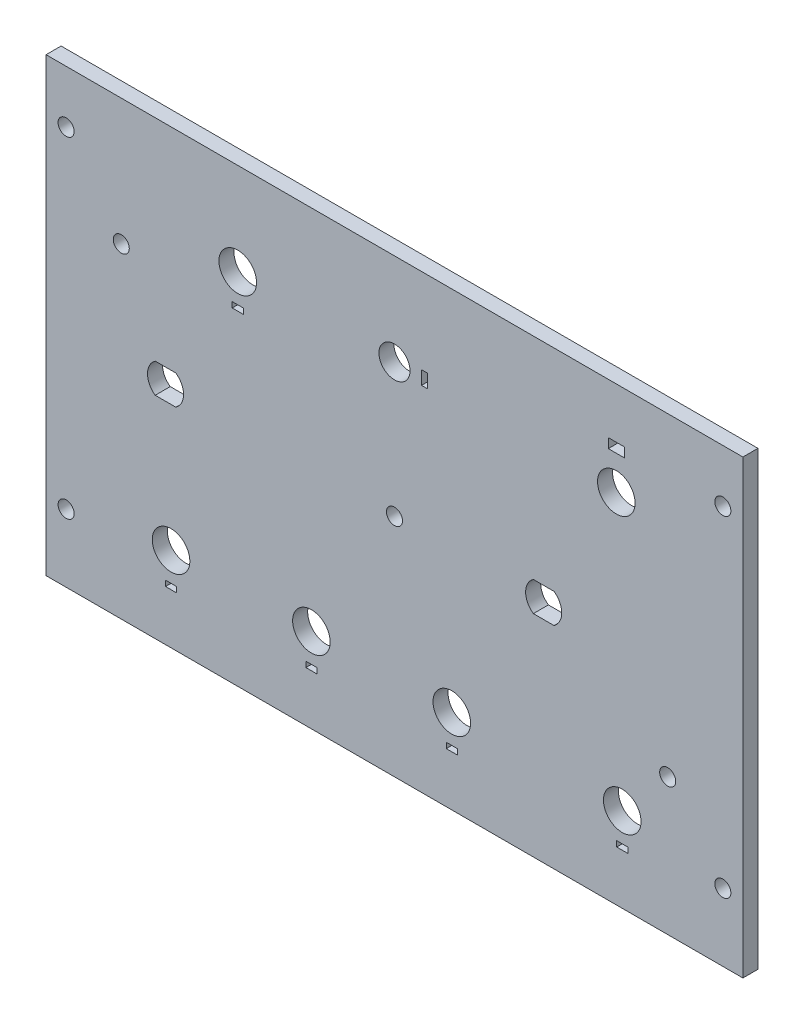
SolidWorks part; units mm, degrees
ref_plane "Front Plane" through (0, 0, 0) normal (0, 0, 1) x (1, 0, 0)
ref_plane "Top Plane" through (0, 0, 0) normal (0, 1, 0) x (1, 0, 0)
ref_plane "Right Plane" through (0, 0, 0) normal (1, 0, 0) x (0, 0, -1)
sketch "Sketch1" plane through (0, 0, 0) normal (0, 0, 1) x (1, 0, 0)
  line L0 (0, 45) -> (139, 45) construction
  line L1 (0, 0) -> (139, 0)
  line L2 (0, 0) -> (0, 90)
  line L3 (0, 90) -> (139, 90)
  line L4 (139, 0) -> (139, 90)
  line L5 (69.5, 90) -> (69.5, 0) construction
  line L8 (38.2351, 71.6142) -> (38.2351, 70.2014) construction
  line L9 (37.1351, 64.8142) -> (39.3351, 64.8142)
  line L10 (37.1351, 64.8142) -> (37.1351, 65.9142)
  line L11 (37.1351, 65.9142) -> (39.3351, 65.9142)
  line L12 (39.3351, 64.8142) -> (39.3351, 65.9142)
  line L13 (37.1351, 64.8142) -> (39.3351, 65.9142) construction
  line L14 (37.1351, 65.9142) -> (39.3351, 64.8142) construction
  line L17 (24.932, 16.842) -> (24.932, 10.592) construction
  line L25 (23.832, 10.042) -> (26.032, 10.042)
  line L26 (23.832, 10.042) -> (23.832, 11.142)
  line L27 (23.832, 11.142) -> (26.032, 11.142)
  line L28 (26.032, 10.042) -> (26.032, 11.142)
  line L29 (23.832, 10.042) -> (26.032, 11.142) construction
  line L30 (23.832, 11.142) -> (26.032, 10.042) construction
  line L31 (52.932, 16.842) -> (52.932, 10.592) construction
  line L32 (51.832, 10.042) -> (54.032, 10.042)
  line L33 (51.832, 10.042) -> (51.832, 11.142)
  line L34 (51.832, 11.142) -> (54.032, 11.142)
  line L35 (54.032, 10.042) -> (54.032, 11.142)
  line L36 (51.832, 10.042) -> (54.032, 11.142) construction
  line L37 (51.832, 11.142) -> (54.032, 10.042) construction
  line L38 (80.932, 16.842) -> (80.932, 10.592) construction
  line L39 (79.832, 10.042) -> (82.032, 10.042)
  line L40 (79.832, 10.042) -> (79.832, 11.142)
  line L41 (79.832, 11.142) -> (82.032, 11.142)
  line L42 (82.032, 10.042) -> (82.032, 11.142)
  line L43 (79.832, 10.042) -> (82.032, 11.142) construction
  line L44 (79.832, 11.142) -> (82.032, 10.042) construction
  line L45 (114.932, 16.842) -> (114.932, 10.592) construction
  line L46 (113.832, 10.042) -> (116.032, 10.042)
  line L47 (113.832, 10.042) -> (113.832, 11.142)
  line L48 (113.832, 11.142) -> (116.032, 11.142)
  line L49 (116.032, 10.042) -> (116.032, 11.142)
  line L50 (113.832, 10.042) -> (116.032, 11.142) construction
  line L51 (113.832, 11.142) -> (116.032, 10.042) construction
  line L52 (97.1984, 42.05) -> (101.3252, 42.05)
  line L57 (101.3252, 47.95) -> (97.1984, 47.95)
  line L66 (69.5, 71.6755) -> (75.5, 71.6755) construction
  line L67 (76.1, 70.3255) -> (76.1, 73.0255)
  line L68 (76.1, 70.3255) -> (74.9, 70.3255)
  line L69 (74.9, 70.3255) -> (74.9, 73.0255)
  line L70 (76.1, 73.0255) -> (74.9, 73.0255)
  line L71 (76.1, 70.3255) -> (74.9, 73.0255) construction
  line L72 (74.9, 70.3255) -> (76.1, 73.0255) construction
  line L73 (115.3516, 79.9255) -> (112.1516, 79.9255)
  line L74 (115.3516, 79.9255) -> (115.3516, 78.0255)
  line L75 (115.3516, 78.0255) -> (112.1516, 78.0255)
  line L76 (112.1516, 79.9255) -> (112.1516, 78.0255)
  line L77 (115.3516, 79.9255) -> (112.1516, 78.0255) construction
  line L78 (115.3516, 78.0255) -> (112.1516, 79.9255) construction
  line L79 (21.7686, 42.05) -> (25.8954, 42.05)
  line L80 (25.8954, 47.95) -> (21.7686, 47.95)
  circle A4 centre (4, 79.5) radius 1.6
  circle A5 centre (135, 79.5) radius 1.6
  circle A6 centre (135, 13.5) radius 1.6
  circle A7 centre (4, 13.5) radius 1.6
  circle A9 centre (15, 64.8142) radius 1.6
  circle A10 centre (38.2351, 71.6142) radius 3.75
  circle A11 centre (124, 27.2514) radius 1.6
  circle A13 centre (24.932, 16.842) radius 3.75
  circle A14 centre (52.932, 16.842) radius 3.75
  circle A15 centre (80.932, 16.842) radius 3.75
  circle A16 centre (114.932, 16.842) radius 3.75
  circle A19 centre (69.5, 71.6755) radius 3.1
  circle A20 centre (113.7516, 71.2755) radius 3.75
  arc A21 (21.7686, 47.95) -> (21.7686, 42.05) centre (23.832, 45) ccw
  arc A22 (25.8954, 42.05) -> (25.8954, 47.95) centre (23.832, 45) ccw
  circle A23 centre (23.832, 45) radius 3.6 construction
  arc A24 (97.1984, 47.95) -> (97.1984, 42.05) centre (99.2618, 45) ccw
  arc A25 (101.3252, 42.05) -> (101.3252, 47.95) centre (99.2618, 45) ccw
  circle A26 centre (69.5, 45) radius 1.6
  point P15 (38.2351, 65.3642)
  point P34 (113.7516, 78.9755)
  point P48 (24.932, 10.592)
  point P57 (52.932, 10.592)
  point P68 (80.932, 10.592)
  point P79 (114.932, 10.592)
  point P116 (75.5, 71.6755)
  dimension "D3" = 13.5
  dimension "D4" = 2.2
  dimension "D5" = 1.1
  dimension "D8" = 3.2
  dimension "D24" = 1.1
  dimension "D25" = 7.5
  dimension "D29" = 7.5
  dimension "D19" = 3.2
  dimension "D31" = 2.2
  dimension "D34" = 5.7
  dimension "D6" = 7.5
  dimension "D21" = 5.9
  dimension "D33" = 7.5
  dimension "D39" = 7.5
  dimension "D52" = 7.5
  dimension "D17" = 7.2
  dimension "D22" = 6.2
  dimension "D1" = 139
  dimension "D2" = 90
  dimension "D7" = 5.7
  dimension "D11" = 131
  dimension "D12" = 4
  dimension "D13" = 10.5
  dimension "D14" = 66
  dimension "D15" = 15
  dimension "D16" = 5.9
  dimension "D18" = 15
  dimension "D20" = 4
  dimension "D23" = 2.2
  dimension "D26" = 5.7
  dimension "D27" = 2.2
  dimension "D28" = 1.1
  dimension "D30" = 5.7
  dimension "D32" = 1.1
  dimension "D35" = 28
  dimension "D36" = 28
  dimension "D37" = 2.2
  dimension "D38" = 1.1
  dimension "D40" = 5.7
  dimension "D41" = 34
  dimension "D42" = 2.7
  dimension "D50" = 1.2
  dimension "D51" = 6
  dimension "D53" = 3.2
  dimension "D54" = 1.9
  dimension "D55" = 7.7
  dimension "D9" = 2
  dimension "D10" = 2
extrude "Boss-Extrude1" add sketch "Sketch1" along normal blind 3
